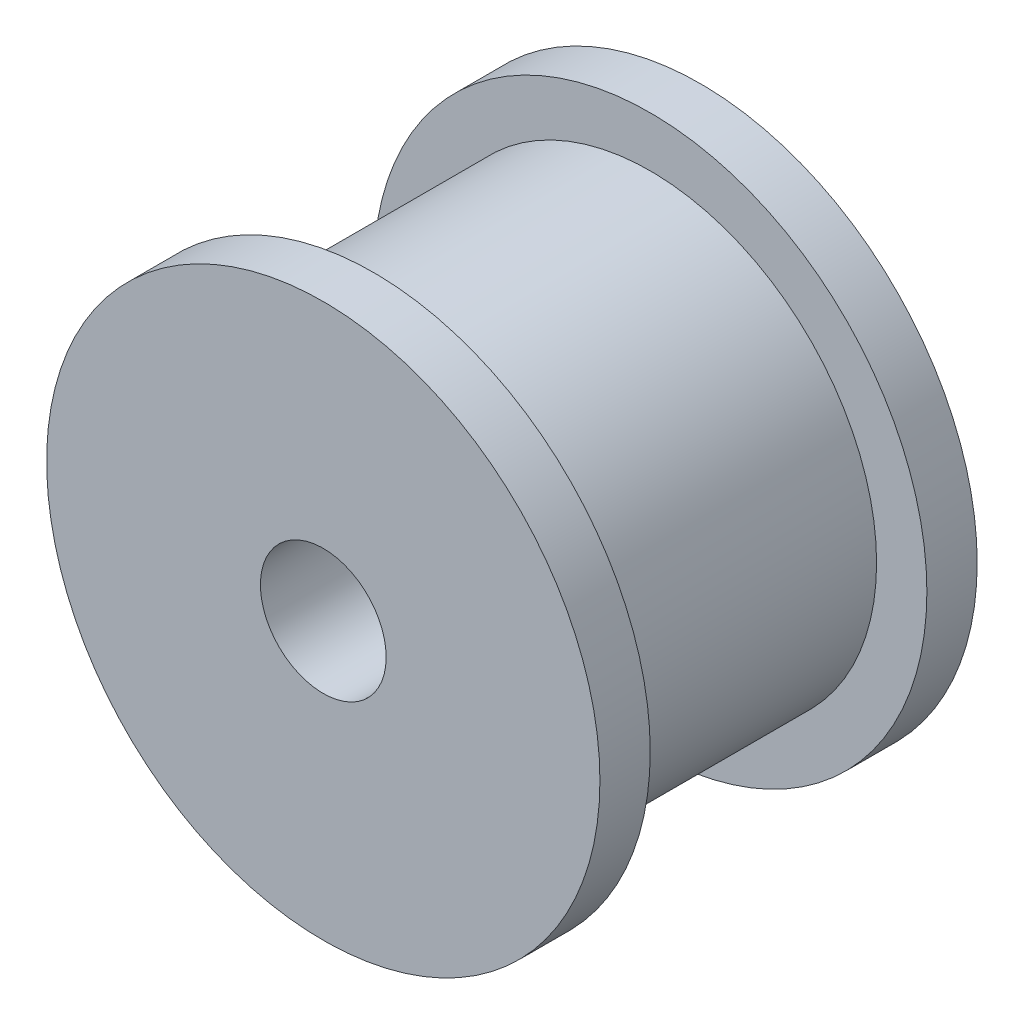
SolidWorks part; units mm, degrees
ref_plane "前视基准面" through (0, 0, 0) normal (0, 0, 1) x (1, 0, 0)
ref_plane "上视基准面" through (0, 0, 0) normal (0, 1, 0) x (1, 0, 0)
ref_plane "右视基准面" through (0, 0, 0) normal (1, 0, 0) x (0, 0, -1)
sketch "草图1" plane through (0, 0, 0) normal (0, 0, 1) x (1, 0, 0)
  circle A0 centre (0, 0) radius 2.5
  circle A1 centre (0, 0) radius 11
  dimension "D1" = 5
  dimension "D2" = 22
extrude "凸台-拉伸1" add sketch "草图1" along normal blind 2
sketch "草图2" plane through (0, 0, 2) normal (0, 0, 1) x (1, 0, 0)
  circle A0 centre (0, 0) radius 2.5
  circle A1 centre (0, 0) radius 9
  dimension "D1" = 5
  dimension "D2" = 18
extrude "凸台-拉伸2" add sketch "草图2" along normal blind 11
sketch "草图3" plane through (0, 0, 13) normal (0, 0, 1) x (1, 0, 0)
  circle A0 centre (0, 0) radius 2.5
  circle A1 centre (0, 0) radius 11
  dimension "D1" = 5
  dimension "D2" = 22
extrude "凸台-拉伸3" add sketch "草图3" along normal blind 2
